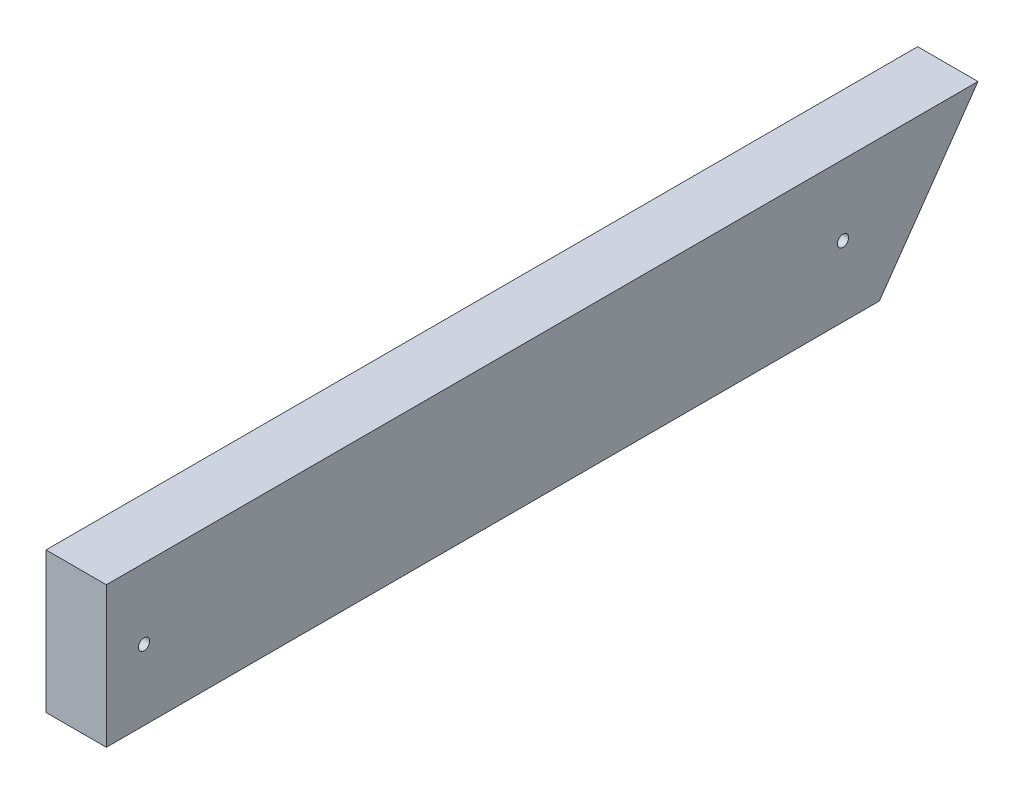
SolidWorks part; units mm, degrees
material "Pine"
ref_plane "Front Plane" through (0, 0, 0) normal (0, 0, 1) x (1, 0, 0)
ref_plane "Top Plane" through (0, 0, 0) normal (0, 1, 0) x (1, 0, 0)
ref_plane "Right Plane" through (0, 0, 0) normal (1, 0, 0) x (0, 0, -1)
sketch "Sketch1" plane through (0, 0, 0) normal (1, 0, 0) x (0, 0, -1)
  line L1 (0, 88.9) -> (550.3862, 88.9)
  line L2 (550.3862, 88.9) -> (488.1378, 0)
  line L3 (488.1378, 0) -> (0, 0)
  line L4 (0, 88.9) -> (0, 0)
  dimension "D1" = 88.9
  dimension "D2" = 55
  dimension "D3" = 88.9
  dimension "D4" = 90
  dimension "D5" = 0
extrude "Boss-Extrude1" add sketch "Sketch1" along normal blind 38.1
sketch "Sketch2" plane through (38.1, 0, 0) normal (1, 0, 0) x (0, 0, -1)
  line L0 (0, 0) -> (488.1378, 0) construction
  line L1 (0, 88.9) -> (0, 0) construction
  line L2 (550.3862, 88.9) -> (0, 88.9) construction
  circle A0 centre (23.8125, 44.45) radius 3.5719
  circle A1 centre (465.1375, 44.45) radius 3.5719
  dimension "D3" = 7.1437
  dimension "D5" = 7.1437
  dimension "D1" = 44.45
  dimension "D2" = 23.8125
  dimension "D4" = 44.45
  dimension "D6" = 465.1375
extrude "Cut-Extrude1" cut sketch "Sketch2" against normal through all
